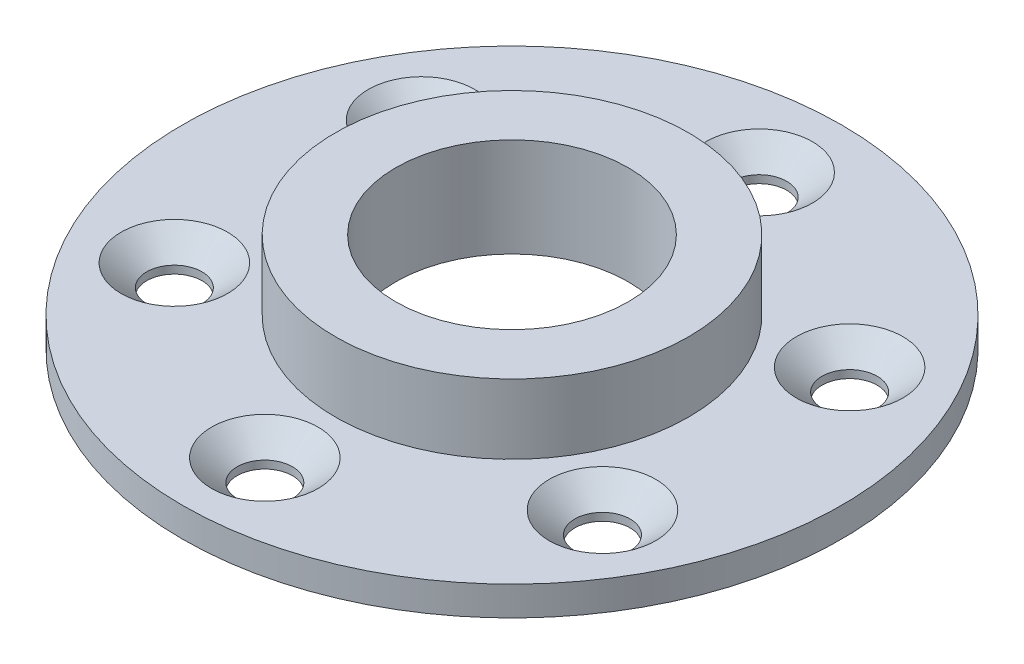
SolidWorks part; units mm, degrees
ref_plane "Front Plane" through (0, 0, 0) normal (0, 0, 1) x (1, 0, 0)
ref_plane "Top Plane" through (0, 0, 0) normal (0, 1, 0) x (1, 0, 0)
ref_plane "Right Plane" through (0, 0, 0) normal (1, 0, 0) x (0, 0, -1)
sketch "Sketch5" plane through (0, 0, 0) normal (0, 1, 0) x (1, 0, 0)
  circle A0 centre (0, 0) radius 90
extrude "Boss-Extrude1" add sketch "Sketch5" along normal blind 8
sketch "Sketch6" plane through (0, 8, 0) normal (0, 1, 0) x (1, 0, 0)
  circle A0 centre (0, 0) radius 40
extrude "Extrude-Thin1" add sketch "Sketch6" along normal blind 19 thin thin type mid plane wall 16.5
sketch "Sketch7" plane through (0, 8, 0) normal (0, 1, 0) x (1, 0, 0)
  line L0 (0, 0) -> (0, 90) construction
  line L1 (0, 45) -> (0, 90) construction
  line L2 (0, 45) -> (0, 90) construction
  circle A0 centre (0, 0) radius 90 construction
  circle A1 centre (0, 67.5) radius 14
  circle A2 centre (67.5, 0) radius 14
  circle A3 centre (0, -67.5) radius 14
  circle A4 centre (-67.5, 0) radius 14
  point P6 (0, 67.5)
  point P11 (0, 67.5)
  dimension "D1" = 4
hole_wizard "CSK for 9/16 Flat Head Machine Screw (100)1" positions "Sketch7" profile "Sketch10" countersink size "9/16" standard "ANSI Inch" end condition through all
sketch "Sketch10" plane through (0, 8, -67.5) normal (1, 0, 0) x (0, 0, 1)
  line L0 (0, 0) -> (0, 8)
  line L1 (0, 8) -> (7.54, 8)
  line L2 (7.54, 8) -> (7.54, 5.875)
  line L3 (7.54, 5.875) -> (14.5415, 0)
  line L5 (14.5415, 0) -> (0, 0)
  line L6 (-7.54, 5.875) -> (-14.5415, 0) construction
  line L11 (0, -6.35) -> (0, 107.95) construction
  dimension "Thru Hole Dia." = 15.08
  dimension "Thru Hole Depth" = 8
  dimension "Near C'Sink Dia." = 29.083
  dimension "Near C'Sink Angle" = 100
ref_point "Point2"
pattern_circular "CirPattern1" count 6 over 360 about axis through (0, 0, 0) along (0, 1, 0) of "CSK for 9/16 Flat Head Machine Screw (100)1"
sketch "Sketch13" plane through (0, 0, 0) normal (0, 0, 1) x (1, 0, 0)
  line L0 (-31.75, 27) -> (0, 27)
  line L1 (0, 27) -> (0, -3.9693)
  line L2 (0, -3.9693) -> (-31.75, -3.9693)
  line L3 (-31.75, -3.9693) -> (-31.75, 27)
revolve "Cut-Revolve1" cut sketch "Sketch13" angle 360 about L1
